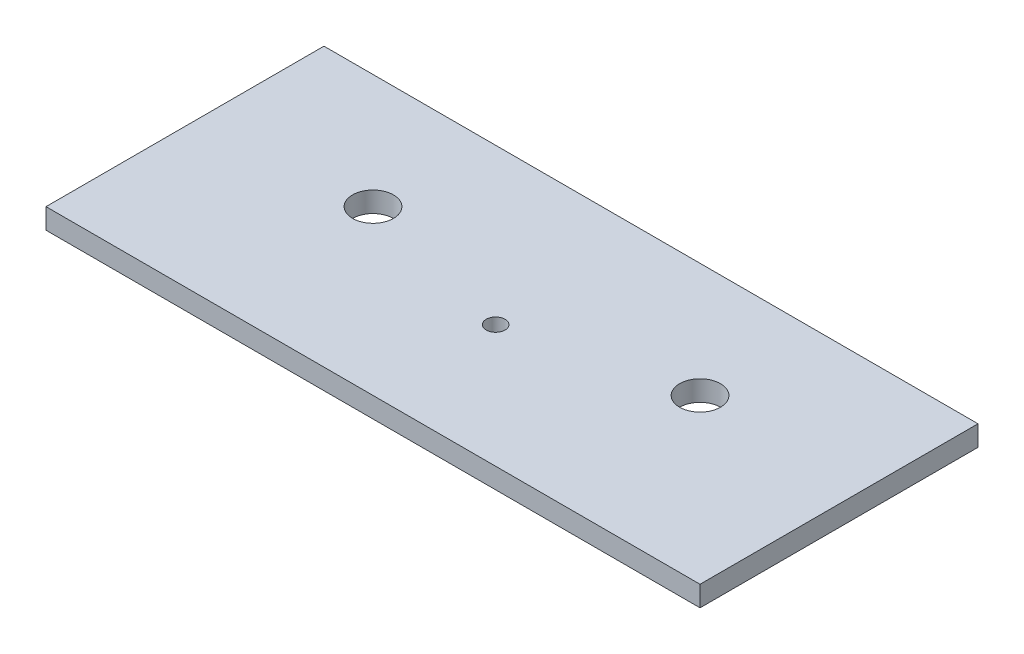
SolidWorks part; units mm, degrees
ref_plane "Front Plane" through (0, 0, 0) normal (0, 0, 1) x (1, 0, 0)
ref_plane "Top Plane" through (0, 0, 0) normal (0, 1, 0) x (1, 0, 0)
ref_plane "Right Plane" through (0, 0, 0) normal (1, 0, 0) x (0, 0, -1)
sketch "Sketch2" plane through (0, 0, 0) normal (0, 1, 0) x (1, 0, 0)
  line L0 (0, -55) -> (0, 55) construction
  line L1 (-50.8, -38.1) -> (50.8, -38.1)
  line L2 (-50.8, -38.1) -> (-50.8, 38.1)
  line L3 (-50.8, 38.1) -> (50.8, 38.1)
  line L4 (50.8, -38.1) -> (50.8, 38.1)
  line L5 (22.225, 0) -> (25.4, 0)
  line L7 (-55, 0) -> (55, 0) construction
  line L10 (-50.8, -38.1) -> (-50.8, 38.1)
  line L19 (0, 0) -> (0, -6.35) construction
  line L20 (-50.8, 17.78) -> (50.8, 17.78)
  line L21 (-50.8, -25.4) -> (50.8, -25.4)
  circle A0 centre (25.4, 0) radius 3.175
  circle A1 centre (-25.4, 0) radius 3.175
  circle A2 centre (0, -6.35) radius 1.4605
  point P1 (0, 0)
  dimension "D4" = 6.35
  dimension "D5" = 2.921
  dimension "D1" = 101.6
  dimension "D2" = 76.2
  dimension "D3" = 6.35
  dimension "D6" = 17.78
  dimension "D7" = 25.4
extrude "Boss-Extrude1" add sketch "Sketch2" along normal blind 3.175
